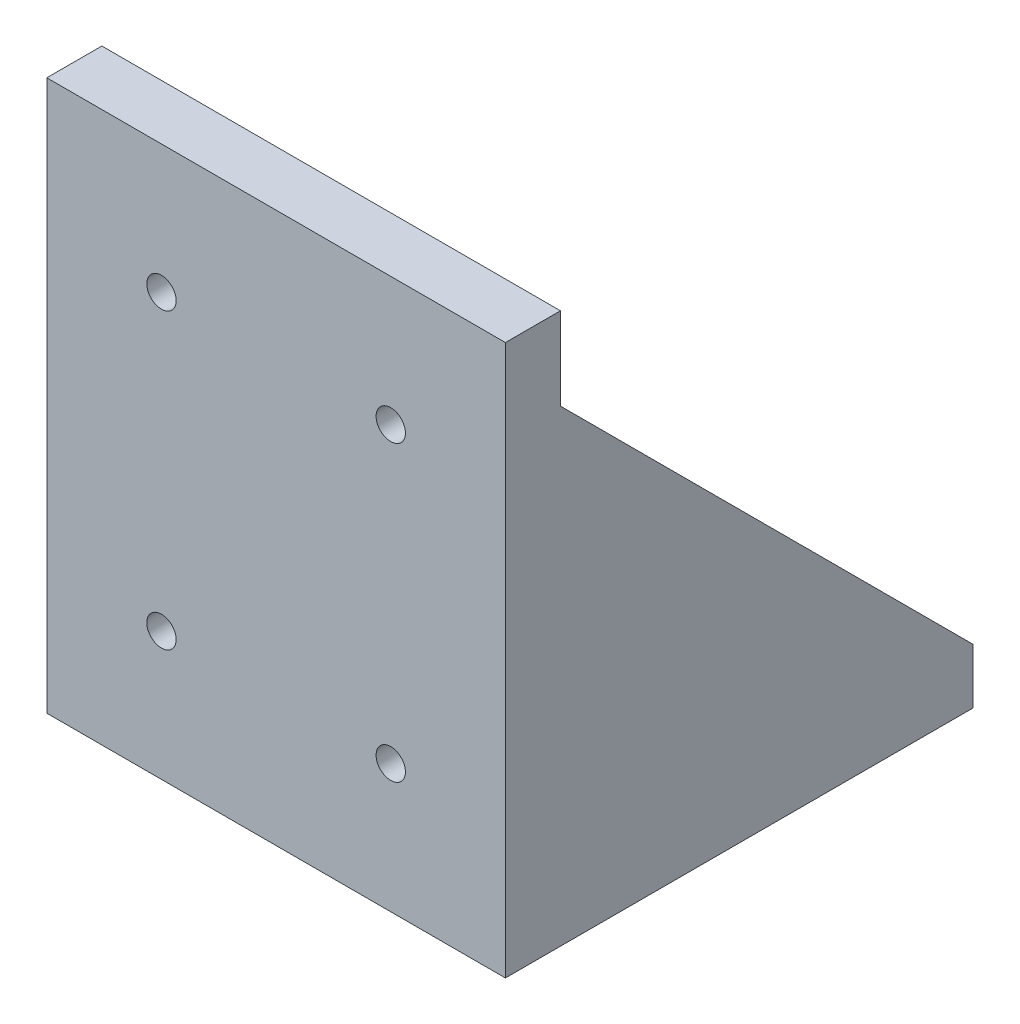
SolidWorks part; units mm, degrees
ref_plane "前视基准面" through (0, 0, 0) normal (0, 0, 1) x (1, 0, 0)
ref_plane "上视基准面" through (0, 0, 0) normal (0, 1, 0) x (1, 0, 0)
ref_plane "右视基准面" through (0, 0, 0) normal (1, 0, 0) x (0, 0, -1)
sketch "草图1" plane through (0, 0, 0) normal (0, 1, 0) x (1, 0, 0)
  line L0 (-25, 23.8) -> (-25, -21.2)
  line L1 (-21.15, -21.15) -> (21.15, -21.15) construction
  line L2 (-21.15, -21.15) -> (-21.15, 21.15) construction
  line L3 (-21.15, 21.15) -> (21.15, 21.15) construction
  line L4 (21.15, -21.15) -> (21.15, 21.15) construction
  line L5 (-21.15, -21.15) -> (21.15, 21.15) construction
  line L6 (-21.15, 21.15) -> (21.15, -21.15) construction
  line L7 (-15.5, -15.5) -> (15.5, -15.5) construction
  line L8 (-15.5, -15.5) -> (-15.5, 15.5) construction
  line L9 (-15.5, 15.5) -> (15.5, 15.5) construction
  line L10 (15.5, -15.5) -> (15.5, 15.5) construction
  line L11 (-15.5, -15.5) -> (15.5, 15.5) construction
  line L12 (-15.5, 15.5) -> (15.5, -15.5) construction
  line L17 (-25, -21.2) -> (25, -21.2)
  line L18 (25, -21.2) -> (25, 23.8)
  line L19 (25, 23.8) -> (-25, 23.8)
  circle A0 centre (-15.5, 15.5) radius 1.65
  circle A1 centre (15.5, 15.5) radius 1.65
  circle A2 centre (15.5, -15.5) radius 1.65
  circle A3 centre (-15.5, -15.5) radius 1.65
  circle A4 centre (0, 0) radius 13
  point P0 (0, 0)
  point P6 (0, 0)
  point P15 (0, 0)
  dimension "D5" = 3.3
  dimension "D6" = 3.3
  dimension "D7" = 3.3
  dimension "D8" = 3.3
  dimension "D9" = 26
  dimension "D1" = 42.3
  dimension "D2" = 42.3
  dimension "D3" = 31
  dimension "D4" = 31
  dimension "D10" = 25
  dimension "D11" = 45
  dimension "D12" = 0.1
  dimension "D13" = 50
extrude "凸台-拉伸1" add sketch "草图1" along normal blind 6
sketch "草图3" plane through (0, 0, 21.2) normal (0, 0, 1) x (1, 0, 0)
  line L1 (-25, 0) -> (25, 0)
  line L2 (-25, 0) -> (-25, 60)
  line L3 (-25, 60) -> (25, 60)
  line L4 (25, 0) -> (25, 60)
  dimension "D1" = 60
extrude "凸台-拉伸2" add sketch "草图3" along normal blind 6
sketch "草图4" plane through (-25, 0, 0) normal (-1, 0, 0) x (0, 0, 1)
  line L0 (-23.8, 6) -> (21.2, 51)
  line L1 (21.2, 60) -> (21.2, 6) construction
  line L2 (21.2, 51) -> (21.2, 6)
  line L3 (21.2, 6) -> (-23.8, 6)
  dimension "D1" = 45
extrude "凸台-拉伸3" add sketch "草图4" against normal blind 3
ref_plane "基准面1" through (0, 0, 0) normal (1, 0, 0) x (0, 0, -1)
mirror "镜向1" about plane through (0, 0, 0) normal (1, 0, 0) of "凸台-拉伸3"
sketch "草图5" plane through (0, 0, 21.2) normal (0, 0, -1) x (-1, 0, 0)
  line L0 (0, 60) -> (0, 0) construction
  line L1 (-25, 60) -> (25, 60) construction
  line L3 (-12.5, 14) -> (12.5, 14) construction
  line L4 (-12.5, 14) -> (-12.5, 46) construction
  line L5 (-12.5, 46) -> (12.5, 46) construction
  line L6 (12.5, 14) -> (12.5, 46) construction
  line L7 (-12.5, 14) -> (12.5, 46) construction
  line L8 (-12.5, 46) -> (12.5, 14) construction
  circle A0 centre (-12.5, 46) radius 1.6
  circle A1 centre (-12.5, 14) radius 1.6
  circle A2 centre (12.5, 14) radius 1.6
  circle A3 centre (12.5, 46) radius 1.6
  point P5 (0, 30)
  dimension "D3" = 3.2
  dimension "D4" = 3.2
  dimension "D1" = 25
  dimension "D2" = 32
extrude "切除-拉伸1" cut sketch "草图5" against normal through all
sketch "草图6" plane through (0, 0, 21.2) normal (0, 0, -1) x (-1, 0, 0)
  circle A0 centre (-12.5, 46) radius 3.5
  circle A1 centre (12.5, 46) radius 3.5
  circle A2 centre (-12.5, 14) radius 3.5
  circle A3 centre (12.5, 14) radius 3.5
  dimension "D1" = 7
  dimension "D2" = 7
  dimension "D3" = 7
  dimension "D4" = 7
extrude "切除-拉伸2" cut sketch "草图6" against normal blind 2
